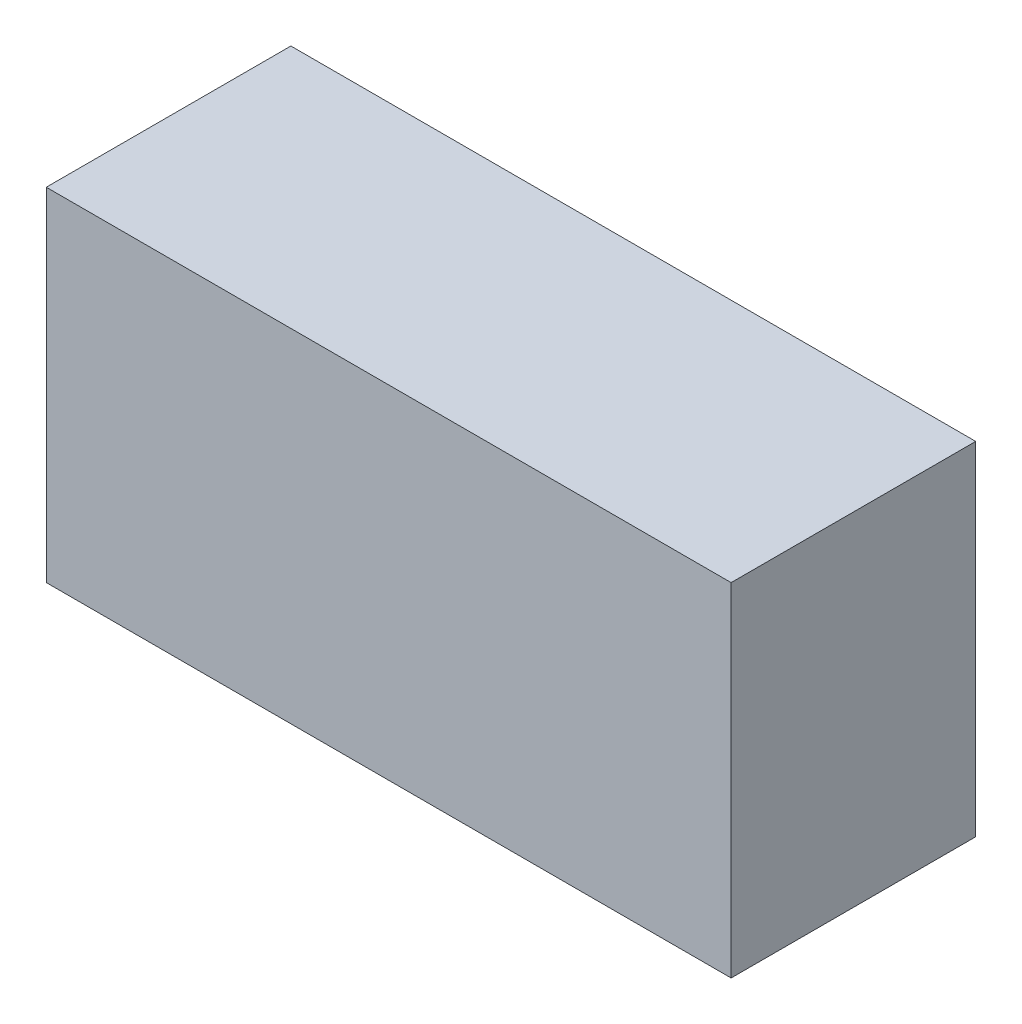
SolidWorks part; units mm, degrees
ref_plane "Front Plane" through (0, 0, 0) normal (0, 0, 1) x (1, 0, 0)
ref_plane "Top Plane" through (0, 0, 0) normal (0, 1, 0) x (1, 0, 0)
ref_plane "Right Plane" through (0, 0, 0) normal (1, 0, 0) x (0, 0, -1)
sketch "Sketch1" plane through (0, 0, 0) normal (0, 0, 1) x (1, 0, 0)
  line L1 (0, 0) -> (70, 0)
  line L2 (0, 0) -> (0, -35)
  line L3 (0, -35) -> (70, -35)
  line L4 (70, 0) -> (70, -35)
extrude "Boss-Extrude1" add sketch "Sketch1" along normal blind 25
